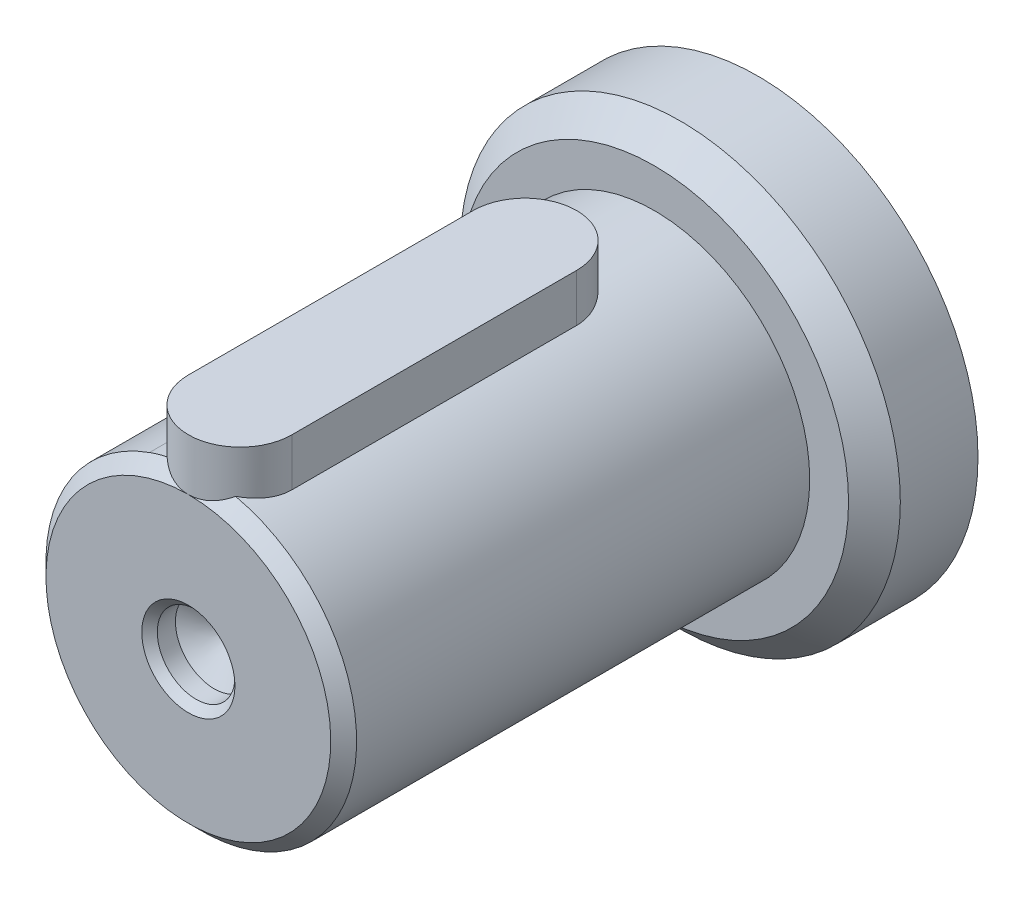
SolidWorks part; units mm, degrees
ref_plane "Plan de face" through (0, 0, 0) normal (0, 0, 1) x (1, 0, 0)
ref_plane "Plan de dessus" through (0, 0, 0) normal (0, 1, 0) x (1, 0, 0)
ref_plane "Plan de droite" through (0, 0, 0) normal (1, 0, 0) x (0, 0, -1)
sketch "Esquisse1" plane through (0, 0, 0) normal (0, 0, 1) x (1, 0, 0)
  circle A0 centre (0, 0) radius 8.5
  dimension "D1" = 17
extrude "Boss.-Extru.1" add sketch "Esquisse1" along normal blind 4
sketch "Esquisse2" plane through (0, 0, 4) normal (0, 0, 1) x (1, 0, 0)
  circle A0 centre (0, 0) radius 6
  dimension "D1" = 12
extrude "Boss.-Extru.2" add sketch "Esquisse2" along normal blind 18
chamfer "Chanfrein1" distance 1 angle 45 1 edges at (8.5, 0, 4)
chamfer "Chanfrein2" distance 0.5 angle 45 1 edges at (6, 0, 22)
ref_plane "Plan1" through (0, 6, 0) normal (0, 1, 0) x (1, 0, 0)
sketch "Esquisse3" plane through (0, 6, 0) normal (0, 1, 0) x (1, 0, 0)
  line L0 (0, -30.6066) -> (0, 7.4045) construction
  line L1 (0, -20) -> (0, -9) construction
  line L2 (-2, -20) -> (-2, -9)
  line L3 (2, -20) -> (2, -9)
  line L4 (-5.5, -22) -> (5.5, -22) construction
  line L5 (-9.0695, -7) -> (12.7701, -7) construction
  line L6 (-9.912, -22) -> (11.8854, -22) construction
  arc A0 (-2, -20) -> (2, -20) centre (0, -20) ccw
  arc A1 (2, -9) -> (-2, -9) centre (0, -9) ccw
  point P5 (0, -14.5)
  dimension "D1" = 4
  dimension "D2" = 15
extrude "Boss.-Extru.3" add sketch "Esquisse3" along normal blind 1.5 and the other way blind 1
hole_wizard "Trous de centrage Ø3.0mm1" positions "Esquisse5" profile "Esquisse4" hole size "Ø3.0" standard "ISO"
sketch "Esquisse5" plane through (0, 0, 22) normal (0, 0, 1) x (1, 0, 0)
  point P0 (0, 0)
sketch "Esquisse4" plane through (0, 0, 22) normal (1, 0, 0) x (0, -1, 0)
  line L0 (0, 0) -> (0, 1.9013)
  line L1 (0, 1.9013) -> (1.5, 1)
  line L2 (1.5, 1) -> (1.5, 0)
  line L5 (1.5, 0) -> (0, 0)
  line L10 (0, 1.9013) -> (-1.5, 1) construction
  line L11 (0, -6.35) -> (0, 107.95) construction
  dimension "Diamètre du perçage" = 3
  dimension "Profondeur du perçage" = 1
  dimension "Angle de pointe" = 118
chamfer "Chanfrein3" distance 0.3 angle 45 1 edges at (1.5, 0, 22)
